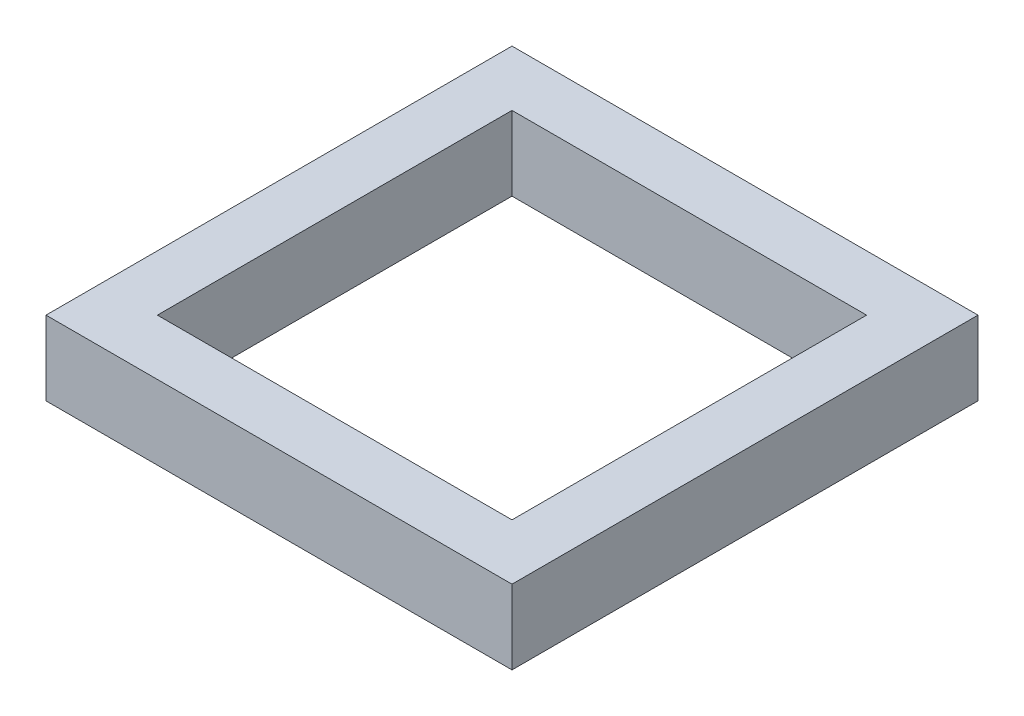
SolidWorks part; units mm, degrees
ref_plane "Front Plane" through (0, 0, 0) normal (0, 0, 1) x (1, 0, 0)
ref_plane "Top Plane" through (0, 0, 0) normal (0, 1, 0) x (1, 0, 0)
ref_plane "Right Plane" through (0, 0, 0) normal (1, 0, 0) x (0, 0, -1)
sketch "Sketch1" plane through (0, 0, 0) normal (0, 1, 0) x (1, 0, 0)
  line L0 (9.55, 9.55) -> (9.55, -9.55)
  line L1 (12.55, -12.55) -> (-12.55, -12.55)
  line L2 (12.55, -12.55) -> (12.55, 12.55)
  line L3 (9.55, -9.55) -> (-9.55, -9.55)
  line L4 (9.55, 9.55) -> (-9.55, 9.55)
  line L5 (-9.55, -9.55) -> (-9.55, 9.55)
  line L6 (12.55, 12.55) -> (-12.55, 12.55)
  line L7 (-12.55, -12.55) -> (-12.55, 12.55)
  line L8 (12.55, -12.55) -> (-12.55, 12.55) construction
  line L9 (12.55, 12.55) -> (-12.55, -12.55) construction
  point P0 (0, 0)
  dimension "D1" = 19.1
  dimension "D2" = 3
extrude "Boss-Extrude1" add sketch "Sketch1" along normal blind 4
